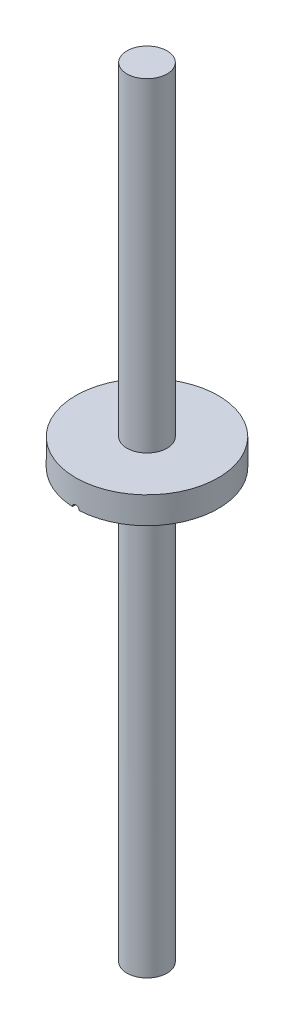
SolidWorks part; units mm, degrees
ref_plane "Front Plane" through (0, 0, 0) normal (0, 0, 1) x (1, 0, 0)
ref_plane "Top Plane" through (0, 0, 0) normal (0, 1, 0) x (1, 0, 0)
ref_plane "Right Plane" through (0, 0, 0) normal (1, 0, 0) x (0, 0, -1)
sketch "Sketch1" plane through (0, 0, 0) normal (0, 1, 0) x (1, 0, 0)
  circle A0 centre (0, 0) radius 16.9291
  dimension "D1" = 33.8582
extrude "Boss-Extrude1" add sketch "Sketch1" along normal blind 6.35
sketch "Sketch2" plane through (0, 0, 0) normal (0, 0, 1) x (1, 0, 0)
  circle A0 centre (0, 0) radius 0.8094
extrude "Cut-Extrude1" cut sketch "Sketch2" against normal through all and the other way through all
sketch "Sketch3" plane through (0, 6.35, 0) normal (0, 1, 0) x (1, 0, 0)
  circle A0 centre (0, 0) radius 4.7625
  dimension "D1" = 9.525
extrude "Boss-Extrude3" add sketch "Sketch3" along normal blind 77 and the other way blind 108
